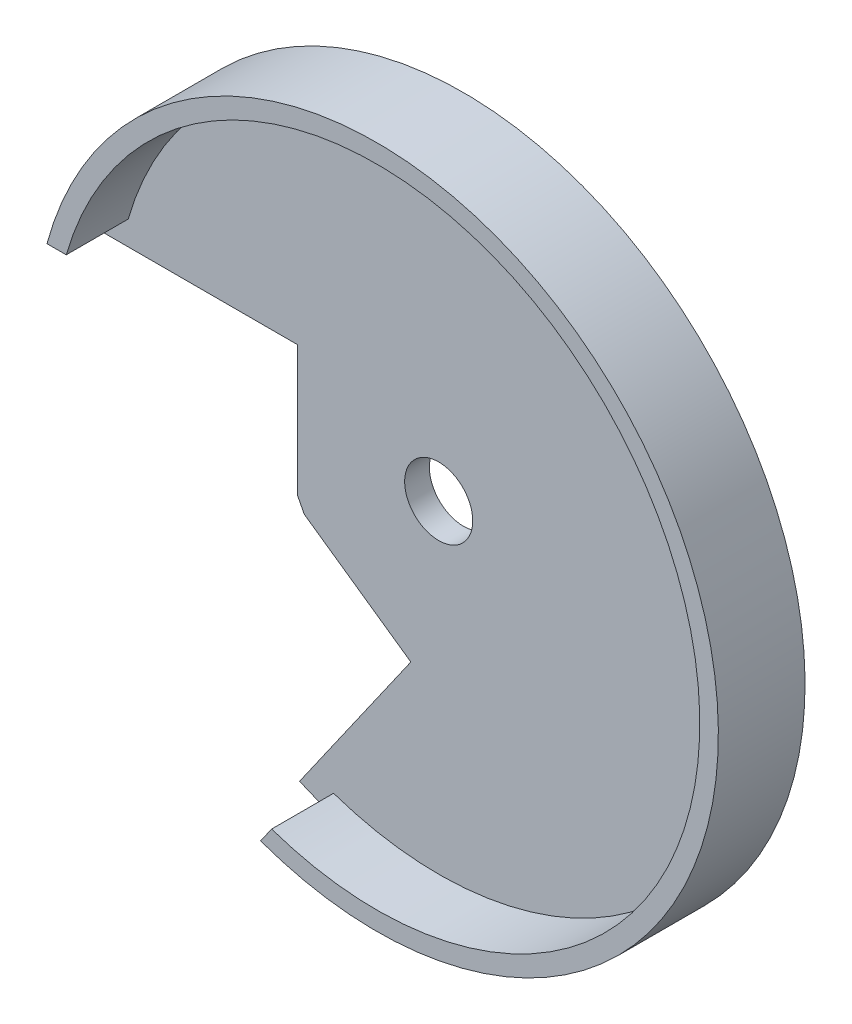
SolidWorks part; units mm, degrees
ref_plane "Front Plane" through (0, 0, 0) normal (0, 0, 1) x (1, 0, 0)
ref_plane "Top Plane" through (0, 0, 0) normal (0, 1, 0) x (1, 0, 0)
ref_plane "Right Plane" through (0, 0, 0) normal (1, 0, 0) x (0, 0, -1)
sketch "Sketch2" plane through (0, 0, 0) normal (0, 0, 1) x (1, 0, 0)
  line L0 (8.8873, 14.4172) -> (-13.2037, 2.9173) construction
  line L1 (-4.3131, 18.7337) -> (-8.6122, 18.7337)
  line L2 (-4.3131, 18.7337) -> (-4.3131, 10.1006)
  line L3 (-4.3131, 10.1006) -> (-8.6122, 10.1006)
  line L4 (-8.6122, 18.7337) -> (-8.6122, 10.1006)
  line L5 (-4.3131, 18.7337) -> (-8.6122, 10.1006) construction
  line L6 (-4.3131, 10.1006) -> (-8.6122, 18.7337) construction
  line L7 (-2.2201, 6.0799) -> (2.3859, -2.3935) construction
  line L8 (4.8518, 1.1281) -> (-4.6859, 2.5582) construction
  line L9 (2.3859, -2.3935) -> (-4.6859, 2.5582)
  line L10 (-2.2201, 6.0799) -> (-4.6859, 2.5582)
  line L11 (4.8518, 1.1281) -> (-2.2201, 6.0799)
  line L12 (4.8518, 1.1281) -> (2.3859, -2.3935)
  circle A0 centre (8.8873, 14.4172) radius 15.35
  circle A1 centre (8.8873, 14.4172) radius 16.55
  point P3 (-6.4627, 14.4172)
  point P14 (0.0829, 1.8432)
  dimension "D2" = 1.2
  dimension "D1" = 55
extrude "Boss-Extrude1" add sketch "Sketch2" along normal blind 3 contours L3 A1 L10 A0 | L12 A1 L1 A0
sketch "Sketch3" plane through (0, 0, 0) normal (0, 0, -1) x (-1, 0, 0)
  circle A0 centre (-8.8873, 14.4172) radius 16.55
  circle A1 centre (-8.8873, 14.4172) radius 1.65
  dimension "D1" = 3.3
extrude "Boss-Extrude2" add sketch "Sketch3" along normal blind 1.2
sketch "Sketch4" plane through (0, 0, 0) normal (0, 0, 1) x (1, 0, 0)
  line L0 (8.8873, 14.4172) -> (-13.2037, 2.9173) construction
  line L1 (2.0373, 17.5672) -> (-14.9627, 17.5672)
  line L2 (2.0373, 17.5672) -> (2.0373, 11.2672)
  line L3 (2.0373, 11.2672) -> (-14.9627, 11.2672)
  line L4 (-14.9627, 17.5672) -> (-14.9627, 11.2672)
  line L5 (2.0373, 17.5672) -> (-14.9627, 11.2672) construction
  line L6 (2.0373, 11.2672) -> (-14.9627, 17.5672) construction
  line L7 (2.378, 10.6127) -> (-2.2121, -6.9264) construction
  line L8 (7.5387, 6.9992) -> (-7.3728, -3.3128) construction
  line L9 (-2.2121, -6.9264) -> (-7.3728, -3.3128)
  line L10 (2.378, 10.6127) -> (-7.3728, -3.3128)
  line L11 (7.5387, 6.9992) -> (2.378, 10.6127)
  line L12 (7.5387, 6.9992) -> (-2.2121, -6.9264)
  line L13 (2.0373, 11.2672) -> (2.378, 10.6127)
  circle A0 centre (8.8873, 14.4172) radius 15.35
  circle A1 centre (8.8873, 14.4172) radius 16.55
  point P3 (-6.4627, 14.4172)
  point P14 (0.0829, 1.8432)
  dimension "D2" = 1.2
  dimension "D1" = 55
  dimension "D3" = 6.3
  dimension "D4" = 17
extrude "Cut-Extrude1" cut sketch "Sketch4" against normal blind 1.2 and the other way blind 7.2 contours L1 A0 L3 L2 | L1 A1 L3 A0 | L10 A1 L12 A0 | L10 A0 L12 L11 | L3 A0 L10 L13 | L3 A1 L10 A0
sketch "Sketch5" plane through (0, 0, 0) normal (0, 0, 1) x (1, 0, 0)
  circle A0 centre (8.8873, 14.4172) radius 15.65
  arc A1 (3.9741, -0.1253) -> (-5.8433, 18.7337) centre (8.8873, 14.4172) ccw construction
  dimension "D1" = 0.3
extrude "Cut-Extrude2" cut sketch "Sketch5" along normal blind 7.2
